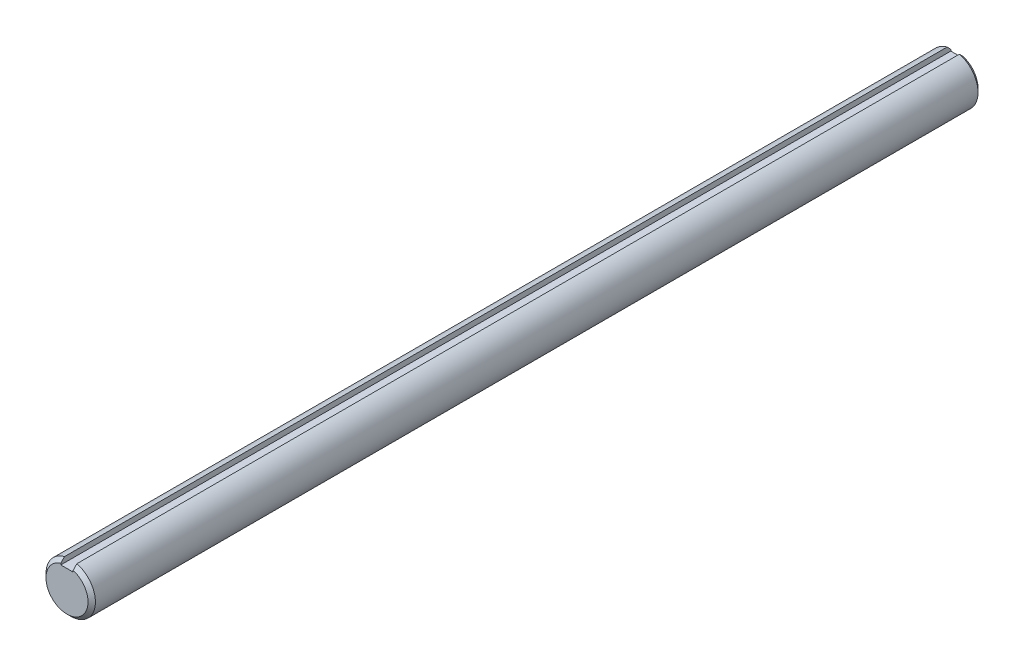
SolidWorks part; units mm, degrees
ref_plane "Front" through (0, 0, 0) normal (0, 0, 1) x (1, 0, 0)
ref_plane "Top" through (0, 0, 0) normal (0, 1, 0) x (1, 0, 0)
ref_plane "Right" through (0, 0, 0) normal (1, 0, 0) x (0, 0, -1)
sketch "Sketch1" plane through (0, 0, 0) normal (0, 0, 1) x (1, 0, 0)
  circle A0 centre (0, 0) radius 6.35
  dimension "dia" = 12.7
extrude "Extrude1" add sketch "Sketch1" along normal mid plane 228.6
sketch "Sketch2" plane through (0, 0, 0) normal (1, 0, 0) x (0, 0, -1)
  point P0 (-114.3, 6.35)
  point P1 (114.3, 6.35)
  point P2 (114.3, -6.35)
chamfer "Chamfer1" distance 0.9525 angle 45 2 edges at (6.35, 0, -114.3) (6.35, 0, 114.3)
sketch "Sketch3" plane through (0, 0, 0) normal (0, 0, 1) x (1, 0, 0)
  line L1 (-1.5875, 6.35) -> (1.5875, 6.35)
  line L2 (-1.5875, 6.35) -> (-1.5875, 4.7625)
  line L3 (-1.5875, 4.7625) -> (1.5875, 4.7625)
  line L4 (1.5875, 6.35) -> (1.5875, 4.7625)
  dimension "key wd" = 3.175
  dimension "key dp" = 1.5875
extrude "Extrude2" cut sketch "Sketch3" against normal through all and the other way through all
equation "\"D1@Chamfer1\" = \"dia@Sketch1\" * .075"
